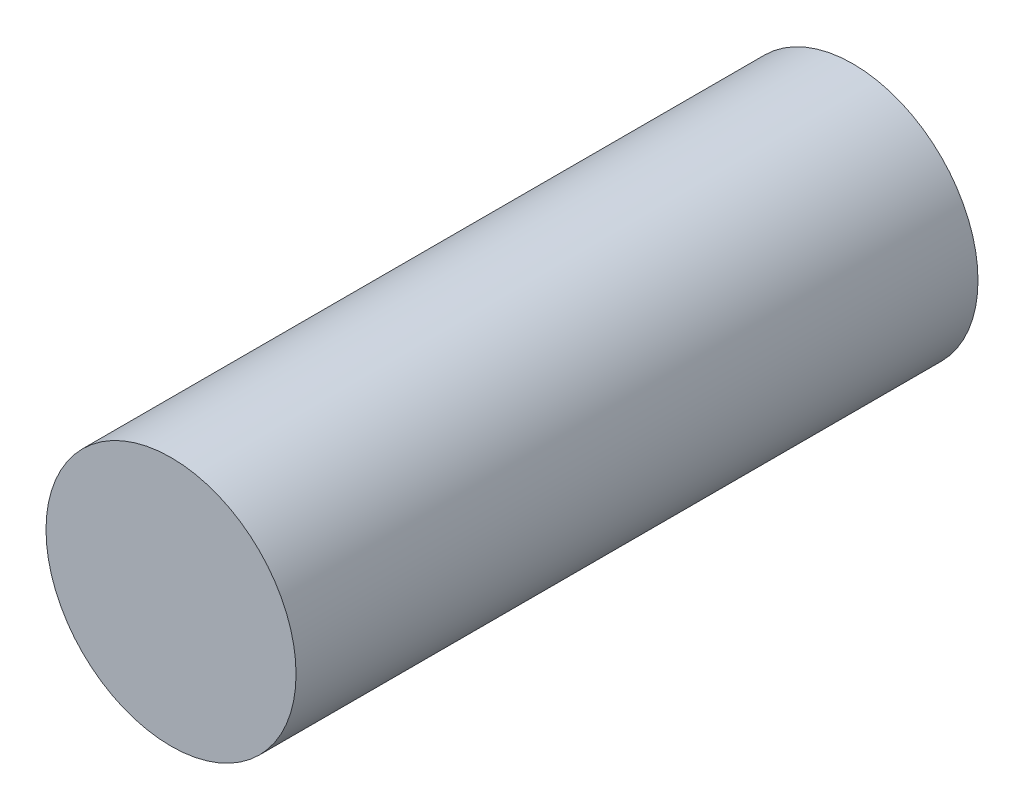
SolidWorks part; units mm, degrees
material "AISI Type A2 Tool Steel"
ref_plane "Front Plane" through (0, 0, 0) normal (0, 0, 1) x (1, 0, 0)
ref_plane "Top Plane" through (0, 0, 0) normal (0, 1, 0) x (1, 0, 0)
ref_plane "Right Plane" through (0, 0, 0) normal (1, 0, 0) x (0, 0, -1)
sketch "Sketch2" plane through (0, 0, 0) normal (0, 0, 1) x (1, 0, 0)
  circle A0 centre (0, 0) radius 5.5
  dimension "D1" = 11
extrude "Boss-Extrude1" add sketch "Sketch2" along normal mid plane 30
